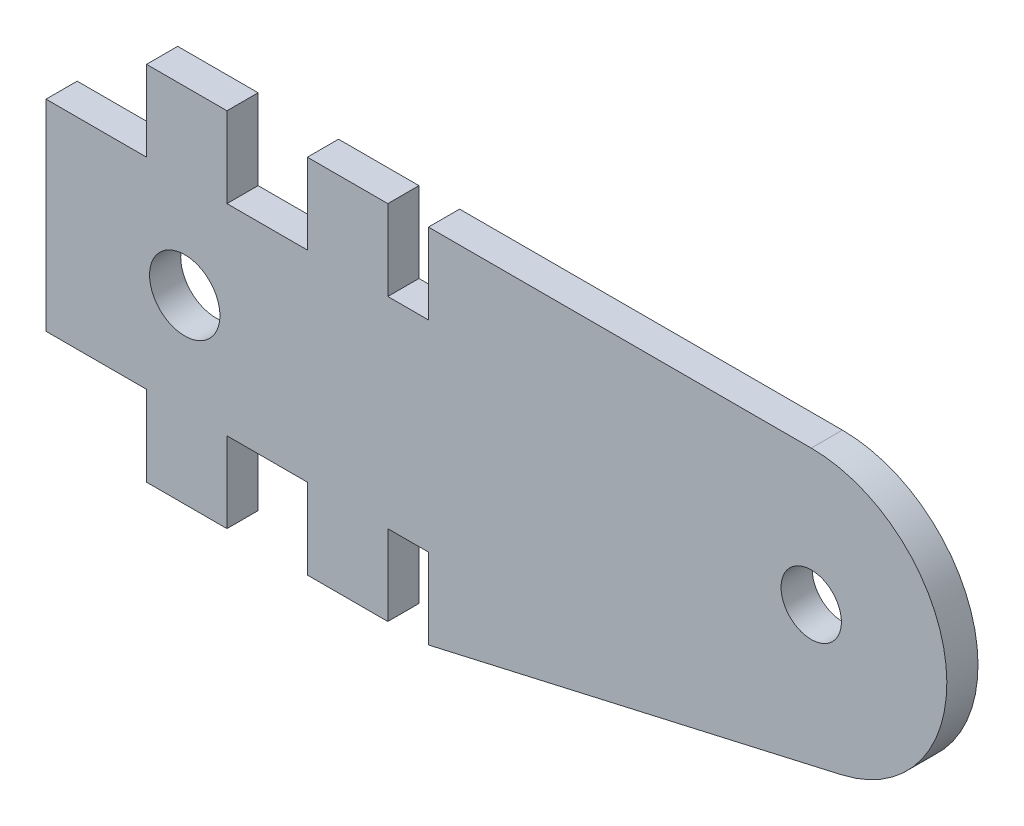
SolidWorks part; units mm, degrees
ref_plane "Front Plane" through (0, 0, 0) normal (0, 0, 1) x (1, 0, 0)
ref_plane "Top Plane" through (0, 0, 0) normal (0, 1, 0) x (1, 0, 0)
ref_plane "Right Plane" through (0, 0, 0) normal (1, 0, 0) x (0, 0, -1)
sketch "Sketch1" plane through (0, 0, 0) normal (0, 0, 1) x (1, 0, 0)
  line L0 (5, 0) -> (9, 0)
  line L1 (5, 4) -> (5, 0)
  line L2 (5, 14) -> (0, 14)
  line L3 (9, 4) -> (13, 4)
  line L4 (13, 4) -> (13, 0)
  line L5 (9, 0) -> (9, 4)
  line L6 (13, 0) -> (17, 0)
  line L7 (17, 0) -> (17, 4)
  line L8 (17, 4) -> (19.0216, 4)
  line L9 (0, 14) -> (0, 4)
  line L10 (19.0216, 4) -> (19.0216, 0)
  line L11 (17, 14) -> (19.0216, 14)
  line L12 (17, 18) -> (17, 14)
  line L13 (13, 18) -> (17, 18)
  line L14 (9, 18) -> (9, 14)
  line L15 (13, 14) -> (13, 18)
  line L16 (9, 14) -> (13, 14)
  line L17 (0, 4) -> (5, 4)
  line L18 (5, 14) -> (5, 18)
  line L19 (5, 18) -> (9, 18)
  line L21 (27.99, 0) -> (27.99, -6.4753) construction
  line L22 (19.0216, 14) -> (19.0216, 18)
  line L25 (15.6441, 12.462) -> (17.6137, 12.1147) construction
  line L26 (16.7455, 7.1907) -> (17.6137, 12.1147) construction
  line L28 (14.7759, 7.538) -> (15.6441, 12.462) construction
  line L29 (16.7455, 7.1907) -> (14.7759, 7.538) construction
  line L30 (23.6391, 5.9751) -> (24.5074, 10.8992) construction
  line L31 (22.5378, 11.2465) -> (24.5074, 10.8992) construction
  line L39 (21.6695, 6.3224) -> (22.5378, 11.2465) construction
  line L40 (23.6391, 5.9751) -> (21.6695, 6.3224) construction
  line L41 (27.99, 18) -> (27.99, 24.4753) construction
  line L42 (19.0216, 0) -> (39.5576, 4.6778)
  line L43 (19.0216, 18) -> (38.0595, 18)
  circle A1 centre (6.9, 9) radius 1.75
  circle A5 centre (38.0595, 11.2546) radius 1.5
  arc A6 (38.0595, 18) -> (39.5576, 4.6778) centre (38.0595, 11.2546) cw
  dimension "D16" = 9
  dimension "D13" = 4.6778
  dimension "D1" = 3.5
  dimension "D2" = 14.7759
  dimension "D7" = 2
  dimension "D12" = 3
  dimension "D15" = 6.7453
  dimension "D3" = 6.9
  dimension "D4" = 16.7455
  dimension "D5" = 7.538
  dimension "D6" = 5
  dimension "D8" = 5
  dimension "D9" = 9
  dimension "D10" = 18
  dimension "D11" = 19.0216
  dimension "ThumbLinkLengthMCP" = 18.99
extrude "Boss-Extrude1" add sketch "Sketch1" along normal blind 1.55
equation "\"ThumbLinkLengthMCP@Sketch1\"= \"HB@parametersSketch@prostheticParameters.SLDPRT\" * 0.211"
